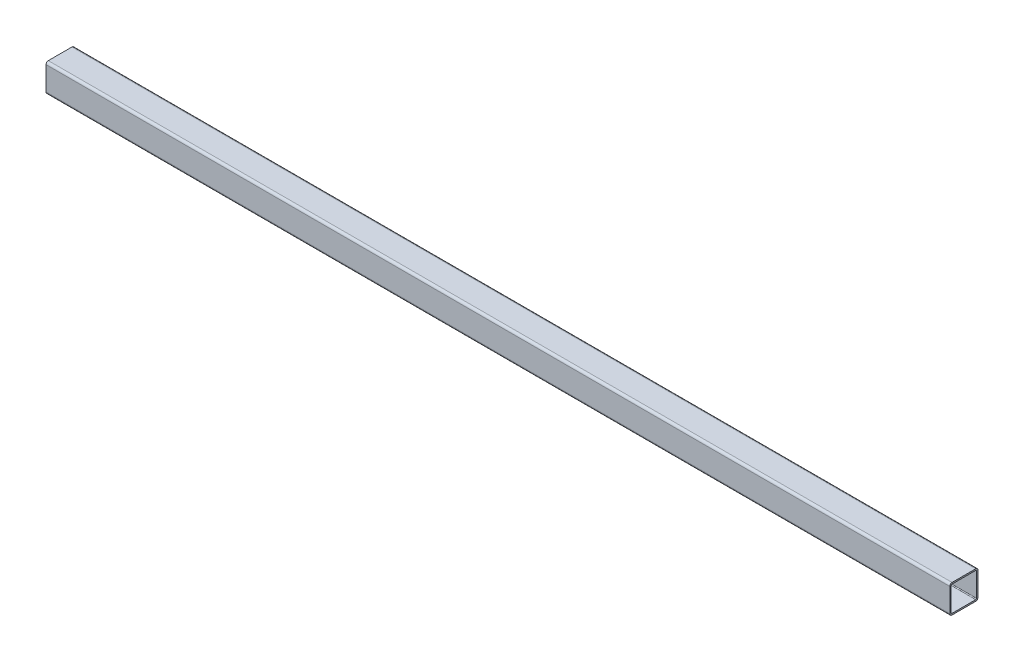
SolidWorks part; units mm, degrees
material "Plain Carbon Steel"
ref_plane "Front Plane" through (0, 0, 0) normal (0, 0, 1) x (1, 0, 0)
ref_plane "Top Plane" through (0, 0, 0) normal (0, 1, 0) x (1, 0, 0)
ref_plane "Right Plane" through (0, 0, 0) normal (1, 0, 0) x (0, 0, -1)
sketch "Sketch1" plane through (0, 0, 0) normal (1, 0, 0) x (0, 0, -1)
  line L0 (-0.1864, 2.5839) -> (-0.1864, 29.1661)
  line L1 (-2.7702, 31.75) -> (-29.3525, 31.75)
  line L2 (-31.9364, 29.1661) -> (-31.9364, 2.5839)
  line L3 (-29.3525, 0) -> (-2.7702, 0)
  line L12 (-1.8374, 2.54) -> (-1.8374, 29.2085)
  line L13 (-2.7279, 30.099) -> (-29.3964, 30.099)
  line L14 (-30.2854, 29.21) -> (-30.2854, 2.5415)
  line L15 (-29.3964, 1.651) -> (-2.7279, 1.651)
  arc A0 (-31.9364, 2.5839) -> (-29.3525, 0) centre (-29.3525, 2.5839) ccw
  arc A1 (-0.1864, 2.5839) -> (-2.7702, 0) centre (-2.7702, 2.5839) cw
  arc A2 (-0.1864, 29.1661) -> (-2.7702, 31.75) centre (-2.7702, 29.1661) ccw
  arc A3 (-31.9364, 29.1661) -> (-29.3525, 31.75) centre (-29.3525, 29.1661) cw
  arc A16 (-1.8374, 2.54) -> (-2.7279, 1.651) centre (-2.7264, 2.54) cw
  arc A17 (-29.3964, 1.651) -> (-30.2854, 2.5415) centre (-29.3964, 2.54) cw
  arc A18 (-1.8374, 29.2085) -> (-2.7279, 30.099) centre (-2.7264, 29.21) ccw
  arc A19 (-30.2854, 29.21) -> (-29.3964, 30.099) centre (-29.3964, 29.21) cw
  point P12 (0, 0)
  point P15 (0, 31.6215)
  point P18 (-31.75, 31.6215)
  point P23 (-30.2854, 1.651)
  dimension "D7" = 2.5839
  dimension "D8" = 0.889
  dimension "D1" = 1.651
  dimension "D2" = 1.651
  dimension "D3" = 1.651
  dimension "D4" = 1.651
  dimension "D5" = 31.75
  dimension "D6" = 31.75
  dimension "D21" = 31.75
  dimension "D9" = 0.1864
  dimension "D10" = 2.7279
  dimension "D11" = 1.651
  dimension "D12" = 31.6215
extrude "Boss-Extrude1" add sketch "Sketch1" along normal blind 609.6
scale "Scale1" bodies to scale 101 scale about centroid uniform scaling no x scale factor 1 y scale factor 0.6 z scale factor 0.6
sketch "Sketch2" plane through (0, 25.4, 0) normal (0, 1, 0) x (1, 0, 0)
  line L0 (0, -8.0867) -> (0, -24.036) construction
  line L1 (609.6, -24.036) -> (0, -24.036) construction
  circle A0 centre (50.9509, -19.2364) radius 3.175
  circle A1 centre (63.3491, -19.2364) radius 3.175
  dimension "D1" = 6.35
  dimension "D2" = 50.9509
  dimension "D3" = 63.3491
  dimension "D4" = 4.7997
extrude "Cut-Extrude1" [suppressed] cut sketch "Sketch2" against normal blind 2.54
equation "\"BeamTickness\"= 0.065in"
equation "\"D1@Sketch1\"=\"BeamTickness\""
equation "\"D2@Sketch1\"=\"BeamTickness\""
equation "\"D3@Sketch1\"=\"BeamTickness\""
equation "\"D4@Sketch1\"=\"BeamTickness\""
